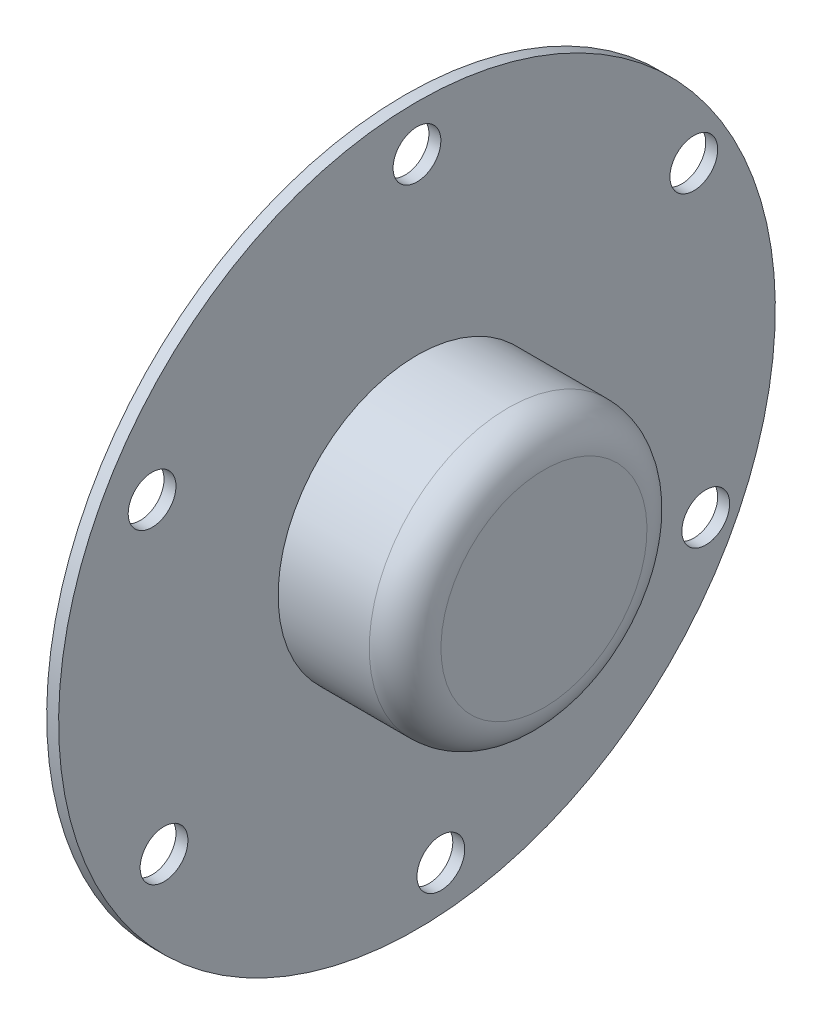
SolidWorks part; units mm, degrees
ref_plane "Front Plane" through (0, 0, 0) normal (0, 0, 1) x (1, 0, 0)
ref_plane "Top Plane" through (0, 0, 0) normal (0, 1, 0) x (1, 0, 0)
ref_plane "Right Plane" through (0, 0, 0) normal (1, 0, 0) x (0, 0, -1)
sketch "Sketch1" plane through (0, 0, 0) normal (0, 0, 1) x (1, 0, 0)
  line L0 (0, 21.25) -> (10.625, 21.25)
  line L1 (0, 21.25) -> (0, 40.625)
  line L3 (10.625, 21.25) -> (10.625, 10.625)
  line L7 (1, 29.25) -> (1, 22.25)
  line L8 (1, 22.25) -> (11.63, 22.25)
  line L9 (11.63, 22.25) -> (11.63, 10.625)
  line L13 (11.63, 10.625) -> (10.625, 10.625)
  line L15 (1, 35.625) -> (1, 29.25)
  line L18 (0, 40.625) -> (1, 40.625)
  line L19 (1, 40.625) -> (1, 35.625)
revolve "Revolve1" add sketch "Sketch1" angle 360 about L13
fillet "Fillet1" radius 3 1 edges at (11.63, 22.25, 0)
sketch "Sketch2" plane through (1, 0, 0) normal (1, 0, 0) x (0, 0, -1)
  circle A0 centre (0, 36.8087) radius 2
  circle A1 centre (23.1758, 24.5829) radius 2
  circle A2 centre (24.1758, -1.6008) radius 2
  circle A3 centre (2, -15.5587) radius 2
  circle A4 centre (-21.1758, -3.3329) radius 2
  circle A5 centre (-22.1758, 22.8508) radius 2
  point P15 (1, 10.625)
  dimension "D1" = 6
extrude "Cut-Extrude1" cut sketch "Sketch2" against normal blind 2
